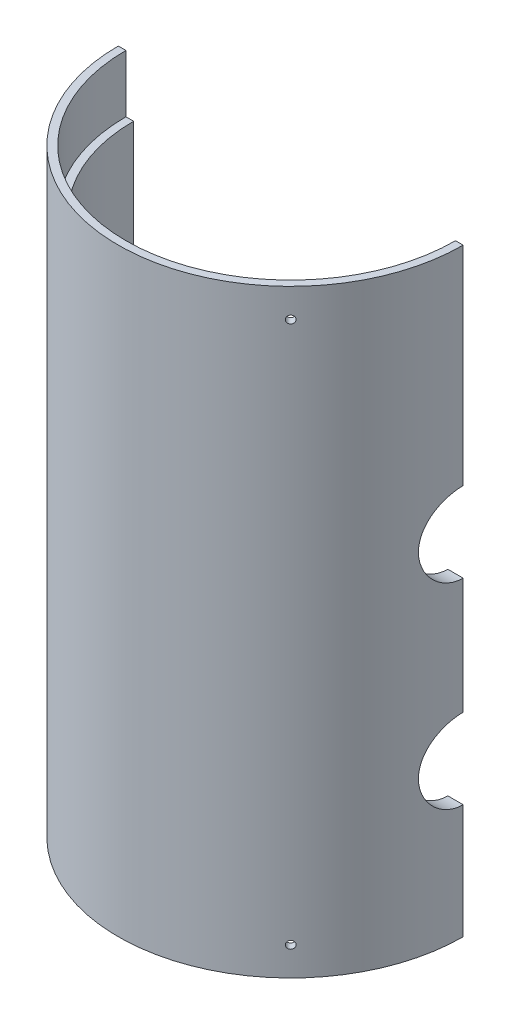
SolidWorks part; units mm, degrees
material "6061-T6 (SS)"
ref_plane "Front Plane" through (0, 0, 0) normal (0, 0, 1) x (1, 0, 0)
ref_plane "Top Plane" through (0, 0, 0) normal (0, 1, 0) x (1, 0, 0)
ref_plane "Right Plane" through (0, 0, 0) normal (1, 0, 0) x (0, 0, -1)
sketch "Sketch1" plane through (0, 0, 0) normal (0, 0, 1) x (1, 0, 0)
  line L0 (0, 0) -> (0, 68.3819) construction
  line L1 (0, 0) -> (-45, 0) construction
  line L2 (-45, 0) -> (-45, 156.3)
  line L3 (-45, 156.3) -> (-43, 156.3)
  line L4 (-43, 156.3) -> (-43, 141.3)
  line L5 (-43, 141.3) -> (-41, 141.3)
  line L6 (-41, 141.3) -> (-41, 15)
  line L7 (-41, 15) -> (-43, 15)
  line L8 (-43, 15) -> (-43, 0)
  line L9 (-43, 0) -> (-45, 0)
  dimension "D1" = 43
  dimension "D2" = 15
  dimension "D3" = 141.3
  dimension "D4" = 41
  dimension "D5" = 45
revolve "Revolve1" add sketch "Sketch1" angle 180 about L0
sketch "Sketch2" plane through (0, 0, 0) normal (1, 0, 0) x (0, 0, -1)
  line L0 (0, 0) -> (0, 6) construction
  line L1 (0, 156.3) -> (0, 0) construction
  line L2 (0, 6) -> (0, 40.3) construction
  line L3 (0, 40.3) -> (0, 91.5) construction
  circle A0 centre (0, 40.3) radius 10.45
  circle A1 centre (0, 91.5) radius 10.45
  dimension "D4" = 20.9
  dimension "D1" = 6
  dimension "D2" = 34.3
  dimension "D3" = 51.2
extrude "Cut-Extrude1" cut sketch "Sketch2" along normal through all
ref_plane "Plane1" through (0, 0, 0) normal (0.7071, 0, -0.7071) x (0, 1, 0)
sketch "Sketch3" plane through (0, 0, 0) normal (0.7071, 0, -0.7071) x (0, 1, 0)
  line L0 (0, 0) -> (7.5, 0) construction
  line L1 (0, 0) -> (68.3819, 0) construction
  line L2 (156.3, -30.4056) -> (156.3, 43) construction
  line L3 (156.3, -30.4056) -> (156.3, 43) construction
  line L4 (156.3, 0) -> (148.8, 0) construction
  circle A0 centre (7.5, 0) radius 1
  circle A1 centre (148.8, 0) radius 1
  dimension "D2" = 2
  dimension "D1" = 7.5
extrude "Cut-Extrude2" cut sketch "Sketch3" against normal through all
pattern_circular "CirPattern1" count 4 over 360 about axis through (0, 0, 0) along (0, -1, 0) of "Cut-Extrude2"
